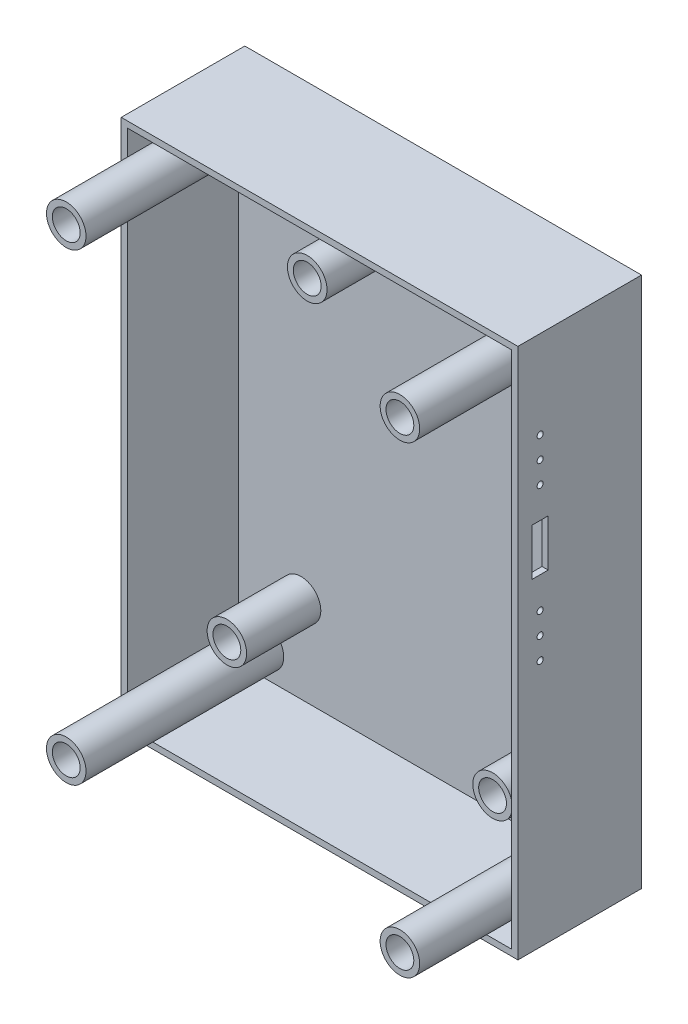
SolidWorks part; units mm, degrees
material "Ст 3 сп 5 ГОСТ 380-94"
ref_plane "Спереди" through (0, 0, 0) normal (0, 0, 1) x (1, 0, 0)
ref_plane "Сверху" through (0, 0, 0) normal (0, 1, 0) x (1, 0, 0)
ref_plane "Справа" through (0, 0, 0) normal (1, 0, 0) x (0, 0, -1)
sketch "Эскиз1" plane through (0, 0, 0) normal (0, 0, 1) x (1, 0, 0)
  line L1 (32.1, -43) -> (-32.1, -43)
  line L2 (32.1, -43) -> (32.1, 43)
  line L3 (32.1, 43) -> (-32.1, 43)
  line L4 (-32.1, -43) -> (-32.1, 43)
  line L5 (32.1, -43) -> (-32.1, 43) construction
  line L6 (32.1, 43) -> (-32.1, -43) construction
  point P0 (0, 0)
extrude "Бобышка-Вытянуть1" add sketch "Эскиз1" along normal blind 20
sketch "Эскиз2" plane through (0, 0, 20) normal (0, 0, 1) x (1, 0, 0)
  line L1 (31.1, -42) -> (-31.1, -42)
  line L2 (31.1, -42) -> (31.1, 42)
  line L3 (31.1, 42) -> (-31.1, 42)
  line L4 (-31.1, -42) -> (-31.1, 42)
  line L5 (31.1, -42) -> (-31.1, 42) construction
  line L6 (31.1, 42) -> (-31.1, -42) construction
  point P0 (0, 0)
extrude "Вырез-Вытянуть1" cut sketch "Эскиз2" against normal blind 18
sketch "Эскиз3" plane through (0, 0, 2) normal (0, 0, 1) x (1, 0, 0)
  line L0 (0, -28) -> (-76.5809, -28) construction
  line L1 (0, 29.5) -> (81.3561, 29.5) construction
  line L2 (-21, -27) -> (-21, -16.3338) construction
  line L3 (-8, 31.3) -> (-8, 56.205) construction
  line L4 (19, 31.3) -> (19, 61.0363) construction
  line L5 (22, -27) -> (22, -60.4255) construction
  circle A1 centre (-21, -28) radius 3.2
  circle A4 centre (22, -28) radius 3.2
  circle A6 centre (19, 29.5) radius 3.2
  circle A7 centre (-8, 29.5) radius 3.2
  dimension "D1" = 28
  dimension "D3" = 21
  dimension "D4" = 13
  dimension "D2" = 57.5
  dimension "D5" = 40
  dimension "D6" = 43
extrude "Бобышка-Вытянуть2" add sketch "Эскиз3" along normal blind 12
sketch "Эскиз6" plane through (0, 0, 14) normal (0, 0, 1) x (1, 0, 0)
  circle A1 centre (-21, -28) radius 2.25
  circle A2 centre (-8, 29.5) radius 2.25
  circle A3 centre (19, 29.5) radius 2.25
  circle A4 centre (22, -28) radius 2.25
extrude "Вырез-Вытянуть4" cut sketch "Эскиз6" against normal blind 8
sketch "Эскиз7" plane through (0, 0, 2) normal (0, 0, 1) x (1, 0, 0)
  line L0 (-27, 0) -> (-27, 45.0542) construction
  line L1 (27, 0) -> (27, 50.0686) construction
  line L2 (-27, -37.5) -> (-20.359, -37.5) construction
  line L3 (27, -37.5) -> (22.2302, -37.5) construction
  line L4 (27, 37.5) -> (15.8116, 37.5) construction
  line L5 (-27, 37.5) -> (-11.8588, 37.5) construction
  circle A0 centre (-27, -37.5) radius 3.2
  circle A1 centre (27, -37.5) radius 3.2
  circle A2 centre (-27, 37.5) radius 3.2
  circle A3 centre (27, 37.5) radius 3.2
  dimension "D3" = 37.5
  dimension "D1" = 27
  dimension "D2" = 27
  dimension "D4" = 37.5
  dimension "D5" = 37.5
  dimension "D6" = 37.5
extrude "Бобышка-Вытянуть3" add sketch "Эскиз7" along normal blind 32
sketch "Эскиз8" plane through (0, 0, 34) normal (0, 0, 1) x (1, 0, 0)
  circle A0 centre (-27, 37.5) radius 2.25
  circle A1 centre (27, 37.5) radius 2.25
  circle A2 centre (27, -37.5) radius 2.25
  circle A3 centre (-27, -37.5) radius 2.25
extrude "Вырез-Вытянуть5" cut sketch "Эскиз8" against normal blind 8
sketch "Эскиз11" plane through (32.1, 0, 0) normal (1, 0, 0) x (0, 0, -1)
  line L0 (-16.4, 21.8) -> (-48.2715, 21.8) construction
  line L1 (-16.4, 25.3) -> (-43.1224, 25.3) construction
  line L2 (-16.4, -12.2404) -> (-16.4, 16.7977) construction
  line L3 (0, -43) -> (0, 43) construction
  line L4 (-17.7, 16.8) -> (-15.1, 16.8)
  line L5 (-17.7, 16.8) -> (-17.7, 9.2)
  line L6 (-17.7, 9.2) -> (-15.1, 9.2)
  line L7 (-15.1, 16.8) -> (-15.1, 9.2)
  line L8 (-17.7, 16.8) -> (-15.1, 9.2) construction
  line L9 (-17.7, 9.2) -> (-15.1, 16.8) construction
  line L10 (-16.4, 28.8) -> (-39.8182, 28.8) construction
  line L11 (-16.4, 4.15) -> (-33.6467, 4.15) construction
  line L12 (-16.4, 0.65) -> (-29.6177, 0.65) construction
  line L13 (-16.4, -2.85) -> (-28.608, -2.85) construction
  circle A0 centre (-16.4, 21.8) radius 0.5
  circle A1 centre (-16.4, 25.3) radius 0.5
  circle A2 centre (-16.4, 28.8) radius 0.5
  circle A3 centre (-16.4, 0.65) radius 0.5
  circle A4 centre (-16.4, 4.15) radius 0.5
  circle A5 centre (-16.4, -2.85) radius 0.5
  point P0 (0, 0)
  point P6 (-15.6, 0)
  point P8 (-16.4, 13)
  dimension "D6" = 8.85
  dimension "D1" = 16.4
  dimension "D2" = 13
  dimension "D3" = 8.8
  dimension "D4" = 12.3
  dimension "D5" = 15.8
  dimension "D7" = 12.35
  dimension "D8" = 15.85
extrude "Вырез-Вытянуть6" cut sketch "Эскиз11" against normal blind 2
